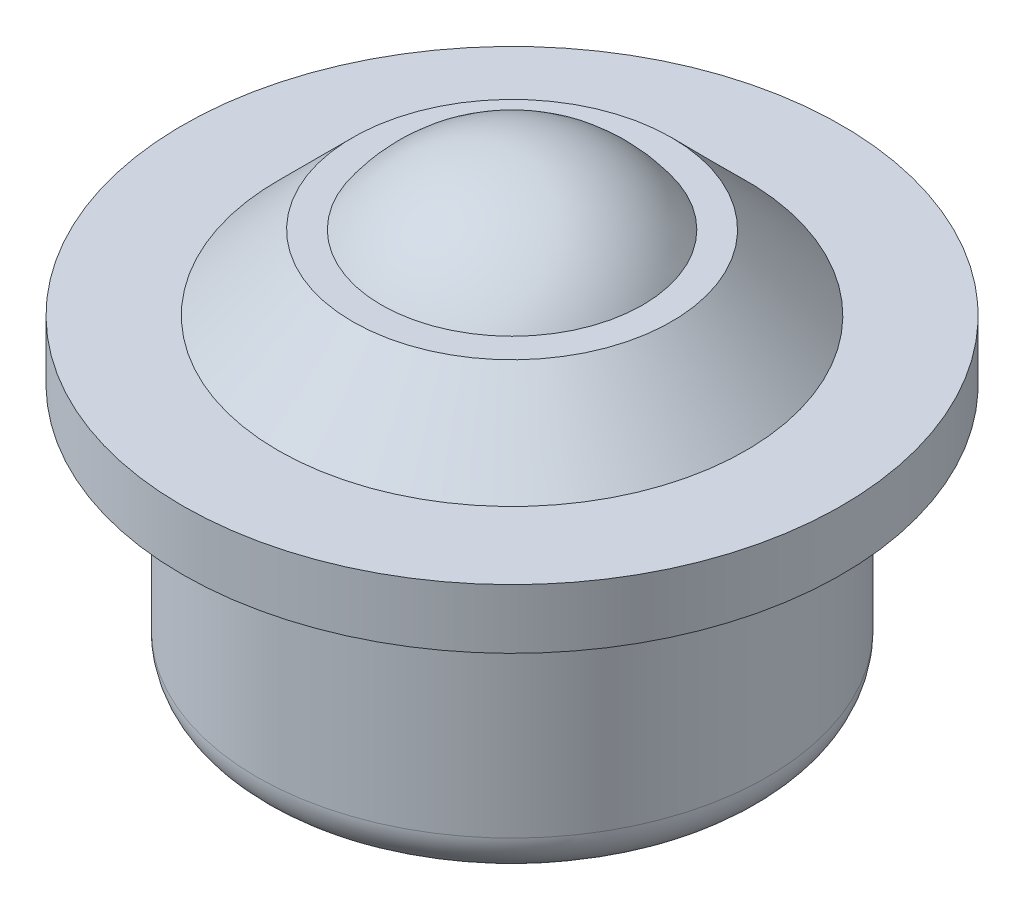
SolidWorks part; units mm, degrees
ref_plane "Plan de face" through (0, 0, 0) normal (0, 0, 1) x (1, 0, 0)
ref_plane "Plan de dessus" through (0, 0, 0) normal (0, 1, 0) x (1, 0, 0)
ref_plane "Plan de droite" through (0, 0, 0) normal (1, 0, 0) x (0, 0, -1)
sketch "Esquisse1" plane through (0, 0, 0) normal (0, 0, 1) x (1, 0, 0)
  line L1 (-12, -2) -> (-15.5, -2)
  line L2 (-11, 0.8) -> (-15.5, 0.8)
  line L3 (-6.1449, 4.3) -> (-7.5, 4.3)
  line L4 (-15.5, 0.8) -> (-15.5, -2)
  line L5 (-12, -2) -> (-12, -12)
  line L6 (0, 7.5) -> (0, -14)
  line L7 (-7.5, 4.3) -> (-11, 0.8)
  arc A0 (0, 7.5) -> (-6.1449, 4.3) centre (0, 0) ccw
  arc A1 (-5.9909, -12.6534) -> (0, -14) centre (0, 0) ccw
  arc A2 (-12, -12) -> (-8.4234, -13.2305) centre (-10, -12) ccw
  arc A3 (-5.9909, -12.6534) -> (-8.4234, -13.2305) centre (-6.8467, -14.4611) ccw
  dimension "D1" = 15
  dimension "D2" = 9.5
  dimension "D5" = 21.5
  dimension "D9" = 4
  dimension "D10" = 2
  dimension "D3" = 6.3
  dimension "D4" = 2.8
  dimension "D6" = 15.5
  dimension "D7" = 12
  dimension "D8" = 1
  dimension "D11" = 45
revolve "Révolution1" add sketch "Esquisse1" angle 360 about L6
